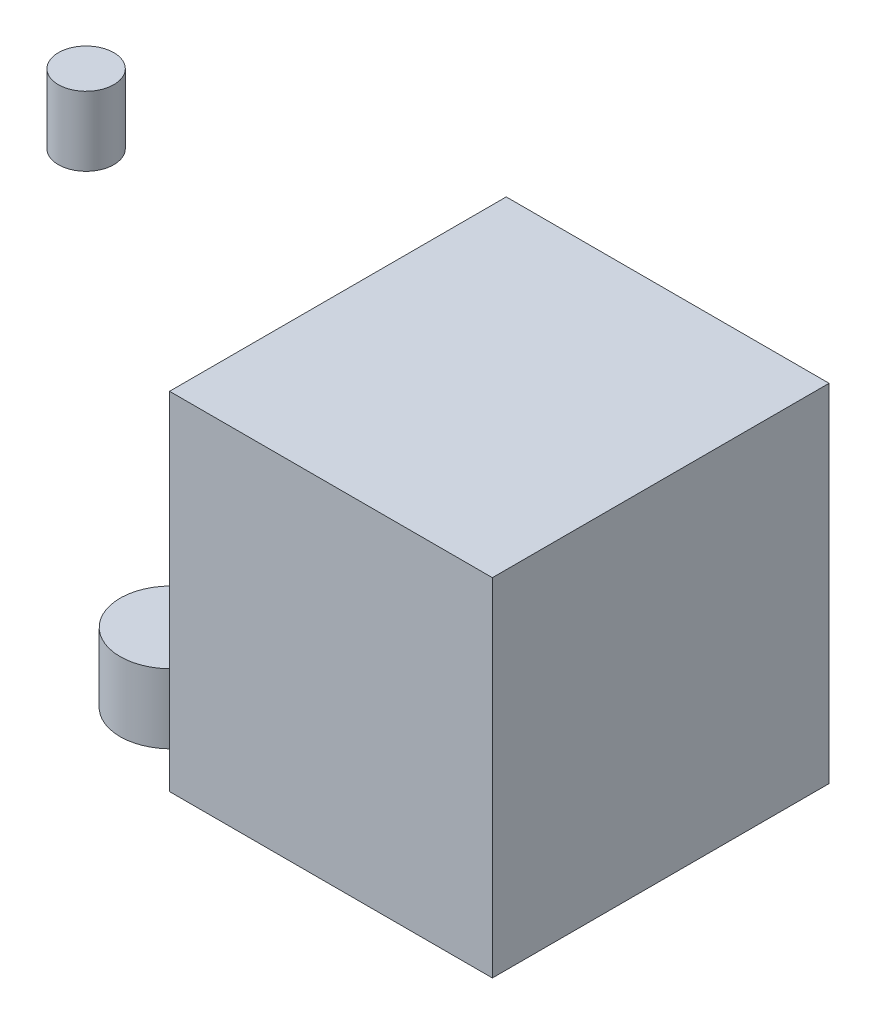
SolidWorks part; units mm, degrees
ref_plane "前视基准面" through (0, 0, 0) normal (0, 0, 1) x (1, 0, 0)
ref_plane "上视基准面" through (0, 0, 0) normal (0, 1, 0) x (1, 0, 0)
ref_plane "右视基准面" through (0, 0, 0) normal (1, 0, 0) x (0, 0, -1)
sketch "草图1" plane through (0, 0, 0) normal (0, 1, 0) x (1, 0, 0)
  line L1 (-23.2789, -24.2781) -> (23.2789, -24.2781)
  line L2 (-23.2789, -24.2781) -> (-23.2789, 24.2781)
  line L3 (-23.2789, 24.2781) -> (23.2789, 24.2781)
  line L4 (23.2789, -24.2781) -> (23.2789, 24.2781)
  line L5 (-23.2789, -24.2781) -> (23.2789, 24.2781) construction
  line L6 (-23.2789, 24.2781) -> (23.2789, -24.2781) construction
  point P0 (0, 0)
extrude "凸台-拉伸1" add sketch "草图1" along normal blind 50
sketch "草图2" plane through (0, 0, 0) normal (0, 1, 0) x (1, 0, 0)
  circle A0 centre (-33.6996, -13.6737) radius 7.3088
  point P2 (-33.6996, -13.6737)
extrude "凸台-拉伸2" add sketch "草图2" along normal blind 10 separate body contours A0
sketch "草图3" plane through (0, 50, 0) normal (0, 1, 0) x (1, 0, 0)
  line L0 (-59.5909, 0) -> (0, 0) construction
  circle A0 centre (-59.5909, 0) radius 4
  dimension "D1" = 8
extrude "凸台-拉伸3" add sketch "草图3" along normal blind 10 separate body
